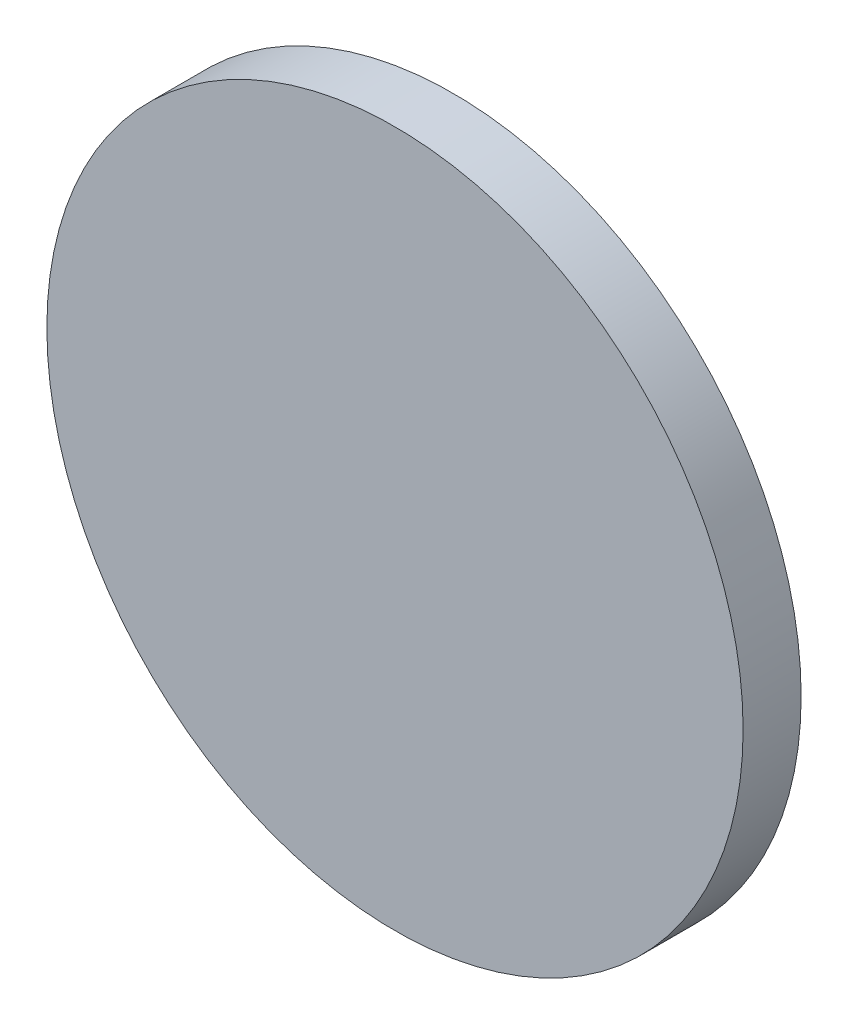
SolidWorks part; units mm, degrees
ref_plane "Front" through (0, 0, 0) normal (0, 0, 1) x (1, 0, 0)
ref_plane "Top" through (0, 0, 0) normal (0, 1, 0) x (1, 0, 0)
ref_plane "Right" through (0, 0, 0) normal (1, 0, 0) x (0, 0, -1)
sketch "Sketch1" plane through (0, 0, 0) normal (0, 0, 1) x (1, 0, 0)
  circle A0 centre (0, 0) radius 114.3
  dimension "D1" = 228.6
extrude "Extrude1" add sketch "Sketch1" along normal blind 19.05
